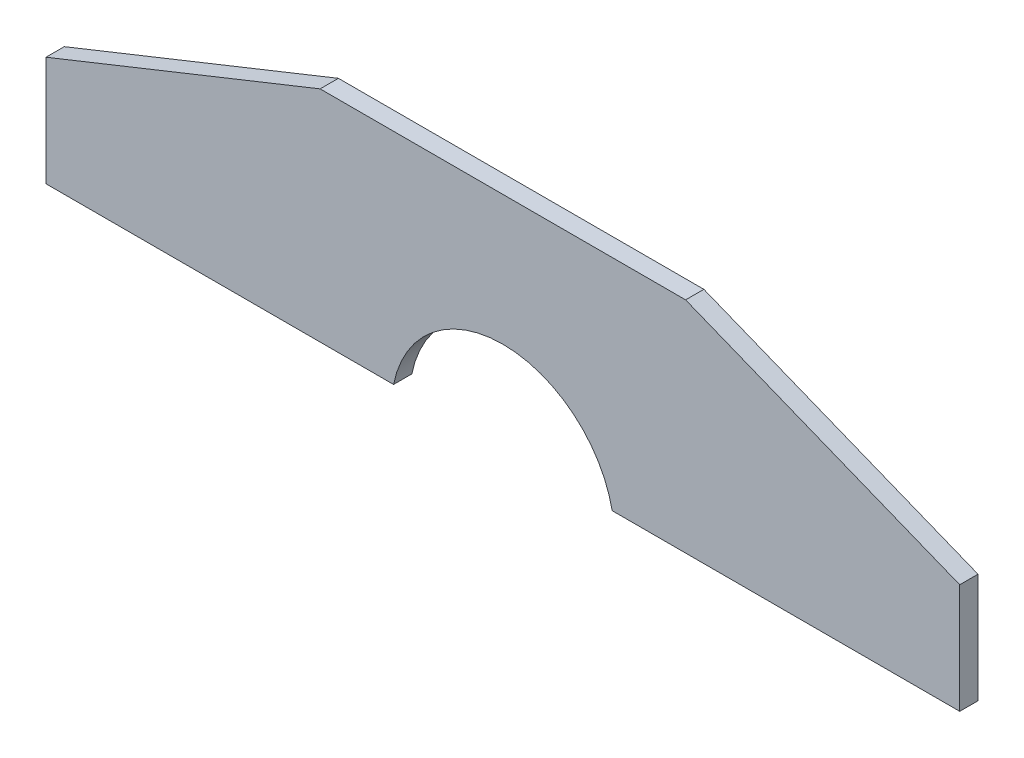
SolidWorks part; units mm, degrees
material "CK45"
ref_plane "Front Plane" through (0, 0, 0) normal (0, 0, 1) x (1, 0, 0)
ref_plane "Top Plane" through (0, 0, 0) normal (0, 1, 0) x (1, 0, 0)
ref_plane "Right Plane" through (0, 0, 0) normal (1, 0, 0) x (0, 0, -1)
sketch "Sketch1" plane through (0, 0, 0) normal (0, 0, 1) x (1, 0, 0)
  line L0 (-125, 36) -> (-50, 66)
  line L1 (-125, 6) -> (-29.904, 6)
  line L2 (-125, 6) -> (-125, 36)
  line L3 (-50, 66) -> (50, 66)
  line L4 (125, 6) -> (125, 36)
  line L5 (50, 66) -> (125, 36)
  line L6 (29.904, 6) -> (125, 6)
  arc A0 (29.904, 6) -> (-29.904, 6) centre (0, 0) ccw
  point P5 (0, 66)
  dimension "D1" = 61
  dimension "D2" = 250
  dimension "D3" = 100
  dimension "D4" = 30
  dimension "D5" = 60
  dimension "D6" = 6
extrude "Boss-Extrude1" add sketch "Sketch1" along normal blind 5
